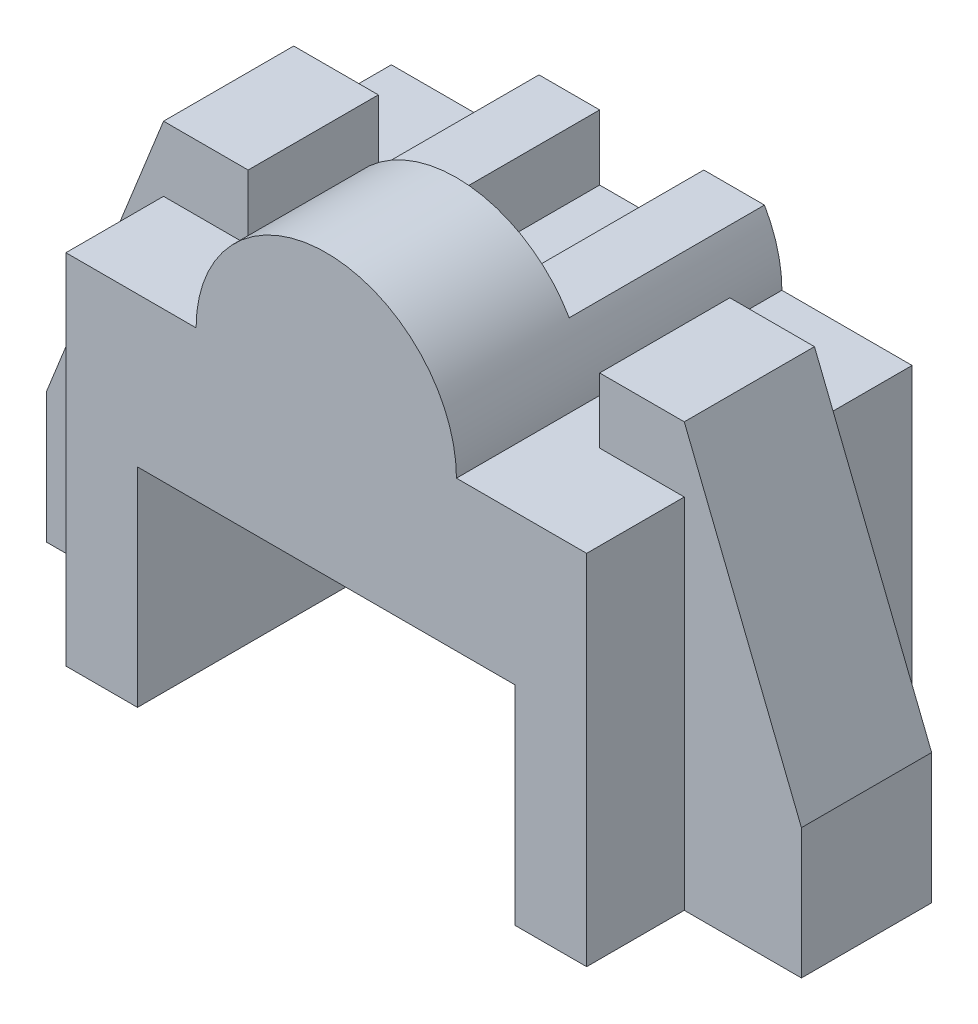
SolidWorks part; units mm, degrees
ref_plane "Front Plane" through (0, 0, 0) normal (0, 0, 1) x (1, 0, 0)
ref_plane "Top Plane" through (0, 0, 0) normal (0, 1, 0) x (1, 0, 0)
ref_plane "Right Plane" through (0, 0, 0) normal (1, 0, 0) x (0, 0, -1)
sketch "Sketch1" plane through (0, 0, 0) normal (0, 0, 1) x (1, 0, 0)
  line L0 (0, 31.7405) -> (0, -41.0811) construction
  line L1 (-54.4, 0) -> (49.2108, 0) construction
  line L2 (-40, -27.5) -> (-40, 27.5)
  line L3 (-40, 27.5) -> (-20, 27.5)
  line L4 (40, 27.5) -> (40, -27.5)
  line L5 (40, -27.5) -> (29, -27.5)
  line L6 (29, -27.5) -> (29, 4.5)
  line L7 (29, 4.5) -> (-29, 4.5)
  line L8 (-29, 4.5) -> (-29, -27.5)
  line L9 (-29, -27.5) -> (-40, -27.5)
  line L10 (-8, 27.5) -> (-8, 37.5)
  line L11 (-8, 27.5) -> (8, 27.5)
  line L12 (8, 37.5) -> (8, 27.5)
  line L13 (-8, 37.5) -> (-17.3205, 37.5)
  line L14 (8, 37.5) -> (17.3205, 37.5)
  line L15 (20, 27.5) -> (40, 27.5)
  arc A0 (20, 27.5) -> (17.3205, 37.5) centre (0, 27.5) ccw
  arc A1 (-17.3205, 37.5) -> (-20, 27.5) centre (0, 27.5) ccw
  dimension "D8" = 40
  dimension "D1" = 32
  dimension "D2" = 55
  dimension "D3" = 27.5
  dimension "D4" = 80
  dimension "D5" = 40
  dimension "D6" = 58
  dimension "D7" = 29
  dimension "D9" = 16
  dimension "D10" = 8
  dimension "D11" = 10
extrude "Boss-Extrude1" add sketch "Sketch1" along normal mid plane 50
sketch "Sketch2" plane through (0, 0, 25) normal (0, 0, 1) x (1, 0, 0)
  line L0 (8, 27.5) -> (-8, 27.5) construction
  line L1 (17.3205, 37.5) -> (8, 37.5) construction
  line L2 (8, 37.5) -> (8, 27.5) construction
  line L3 (-8, 27.5) -> (-8, 37.5) construction
  line L4 (-8, 37.5) -> (-17.3205, 37.5) construction
  line L5 (17.3205, 37.5) -> (8, 37.5)
  line L6 (8, 37.5) -> (8, 27.5)
  line L7 (8, 27.5) -> (-8, 27.5)
  line L8 (-8, 27.5) -> (-8, 37.5)
  line L9 (-8, 37.5) -> (-17.3205, 37.5)
  arc A0 (17.3205, 37.5) -> (-17.3205, 37.5) centre (0, 27.5) ccw
extrude "Boss-Extrude2" add sketch "Sketch2" against normal blind 20
sketch "Sketch3" plane through (0, 0, 0) normal (0, 0, 1) x (1, 0, 0)
  line L0 (-40, 27.5) -> (-40, -27.5) construction
  line L1 (-40, 27.5) -> (-40, -27.5)
  line L2 (-40, -27.5) -> (-58, -27.5)
  line L3 (-58, -27.5) -> (-58, -7.5)
  line L4 (-58, -7.5) -> (-40, 37.5)
  line L5 (-40, 37.5) -> (-27, 37.5)
  line L6 (-27, 37.5) -> (-27, 27.5)
  line L7 (-20, 27.5) -> (-40, 27.5) construction
  line L8 (-27, 27.5) -> (-40, 27.5)
  line L9 (0, 54.9316) -> (0, -38.3513) construction
  line L10 (27, 27.5) -> (40, 27.5)
  line L11 (27, 37.5) -> (27, 27.5)
  line L12 (40, 37.5) -> (27, 37.5)
  line L13 (58, -7.5) -> (40, 37.5)
  line L14 (58, -27.5) -> (58, -7.5)
  line L15 (40, -27.5) -> (58, -27.5)
  line L16 (40, 27.5) -> (40, -27.5)
  dimension "D1" = 58
  dimension "D2" = 20
  dimension "D3" = 10
  dimension "D4" = 13
  dimension "D5" = 40
extrude "Boss-Extrude3" add sketch "Sketch3" along normal mid plane 20
